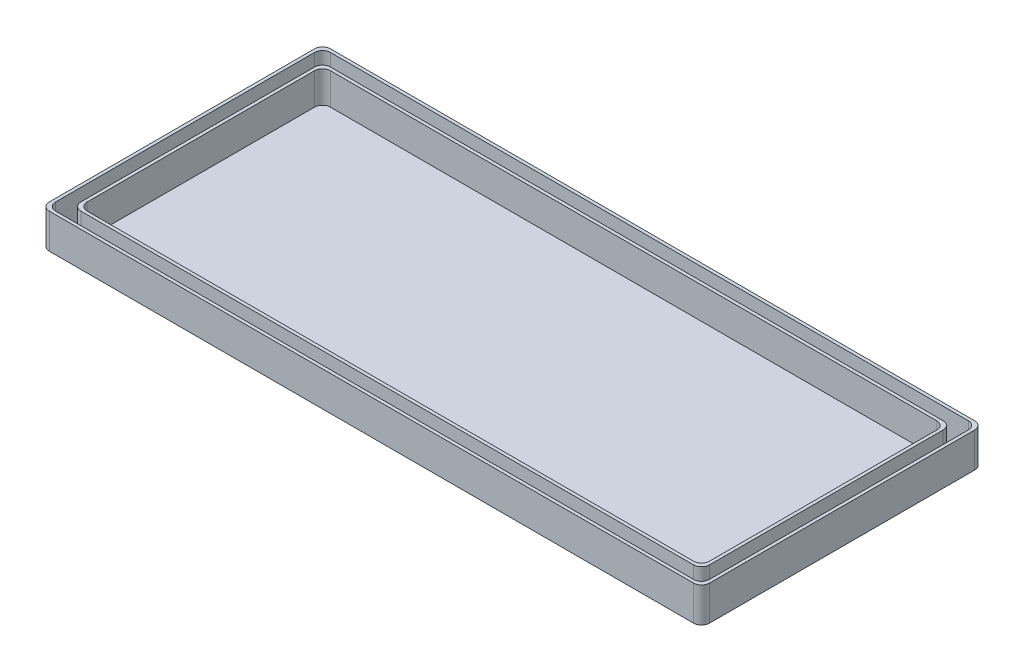
SolidWorks part; units mm, degrees
ref_plane "Plano frontal" through (0, 0, 0) normal (0, 0, 1) x (1, 0, 0)
ref_plane "Plano superior" through (0, 0, 0) normal (0, 1, 0) x (1, 0, 0)
ref_plane "Plano direito" through (0, 0, 0) normal (1, 0, 0) x (0, 0, -1)
sketch "Esboço1" plane through (0, 0, 0) normal (0, 1, 0) x (1, 0, 0)
  line L1 (41.4, -17.4) -> (-41.4, -17.4)
  line L2 (41.4, -17.4) -> (41.4, 17.4)
  line L3 (41.4, 17.4) -> (-41.4, 17.4)
  line L4 (-41.4, -17.4) -> (-41.4, 17.4)
  line L5 (41.4, -17.4) -> (-41.4, 17.4) construction
  line L6 (41.4, 17.4) -> (-41.4, -17.4) construction
  point P0 (0, 0)
  dimension "D1" = 82.8
  dimension "D2" = 34.8
extrude "Ressalto-extrusão1" add sketch "Esboço1" along normal blind 4
shell "Casca2" thickness 0.4
sketch "Esboço2" plane through (0, 0, 0) normal (0, 1, 0) x (1, 0, 0)
  line L4 (-39.4, 15.4) -> (-39.4, -15.4)
  line L5 (-39.4, -15.4) -> (39.4, -15.4)
  line L6 (39.4, -15.4) -> (39.4, 15.4)
  line L7 (39.4, 15.4) -> (-39.4, 15.4)
  line L12 (-39.8, 15.8) -> (-39.8, -15.8)
  line L13 (-39.8, -15.8) -> (39.8, -15.8)
  line L14 (39.8, -15.8) -> (39.8, 15.8)
  line L15 (39.8, 15.8) -> (-39.8, 15.8)
  line L16 (-39.8, 15.8) -> (-39.8, -15.8)
  line L17 (-39.8, -15.8) -> (39.8, -15.8)
  line L18 (39.8, -15.8) -> (39.8, 15.8)
  line L19 (39.8, 15.8) -> (-39.8, 15.8)
  dimension "D1" = 1.6
  dimension "D2" = 0.4
extrude "Ressalto-extrusão2" add sketch "Esboço2" along normal blind 4
fillet "Filete1" radius 1 16 edges at (39.4, 2, 15.4) (-39.4, 2, 15.4) (-39.8, 2, 15.8) (-41.4, 2, 17.4) (-41.8, 1.8, 17.8) (41.4, 2, 17.4) (39.8, 2, 15.8) (41.8, 1.8, 17.8) (41.8, 1.8, -17.8) (41.4, 2, -17.4) (39.4, 2, -15.4) (39.8, 2, -15.8) (-39.8, 2, -15.8) (-41.8, 1.8, -17.8) (-41.4, 2, -17.4) (-39.4, 2, -15.4)
